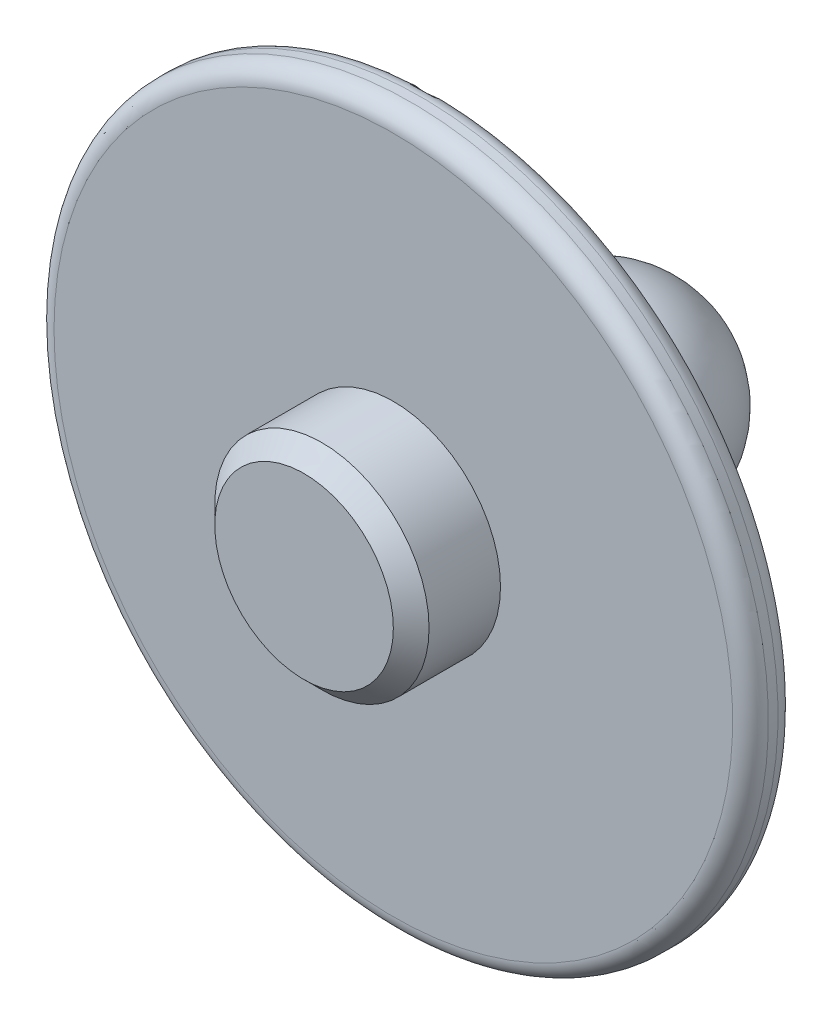
SolidWorks part; units mm, degrees
ref_plane "前视基准面" through (0, 0, 0) normal (0, 0, 1) x (1, 0, 0)
ref_plane "上视基准面" through (0, 0, 0) normal (0, 1, 0) x (1, 0, 0)
ref_plane "右视基准面" through (0, 0, 0) normal (1, 0, 0) x (0, 0, -1)
sketch "草图1" plane through (0, 0, 0) normal (0, 0, 1) x (1, 0, 0)
  circle A0 centre (0, 0) radius 6
  dimension "D1" = 12
extrude "凸台-拉伸1" add sketch "草图1" along normal blind 5
sketch "草图2" plane through (0, 0, 0) normal (1, 0, 0) x (0, 0, -1)
  line L0 (0, 0) -> (11.5, 0) construction
  line L1 (2.75, 0) -> (-2.75, 0) construction
  line L2 (0, 0) -> (0, 20)
  line L3 (0, 6.6) -> (0, -6.6) construction
  line L4 (0, 20) -> (2.174, 20)
  line L5 (2.174, 20) -> (8.9643, 5.4379)
  line L7 (-5, 6) -> (-5, -6) construction
  line L8 (11.5, 0) -> (21.5772, 0) construction
  line L9 (0, 0) -> (17.5, 0)
  arc A0 (17.5, 0) -> (8.9643, 5.4379) centre (11.5, 0) ccw
  dimension "D4" = 6
  dimension "D1" = 2.174
  dimension "D2" = 40
  dimension "D3" = 16.5
revolve "旋转1" add sketch "草图2" angle 360 about L9
chamfer "倒角1" distance 1 angle 45 1 edges at (6, 0, 5)
fillet "圆角1" radius 1 2 edges at (20, 0, -2.174) (20, 0, 0)
